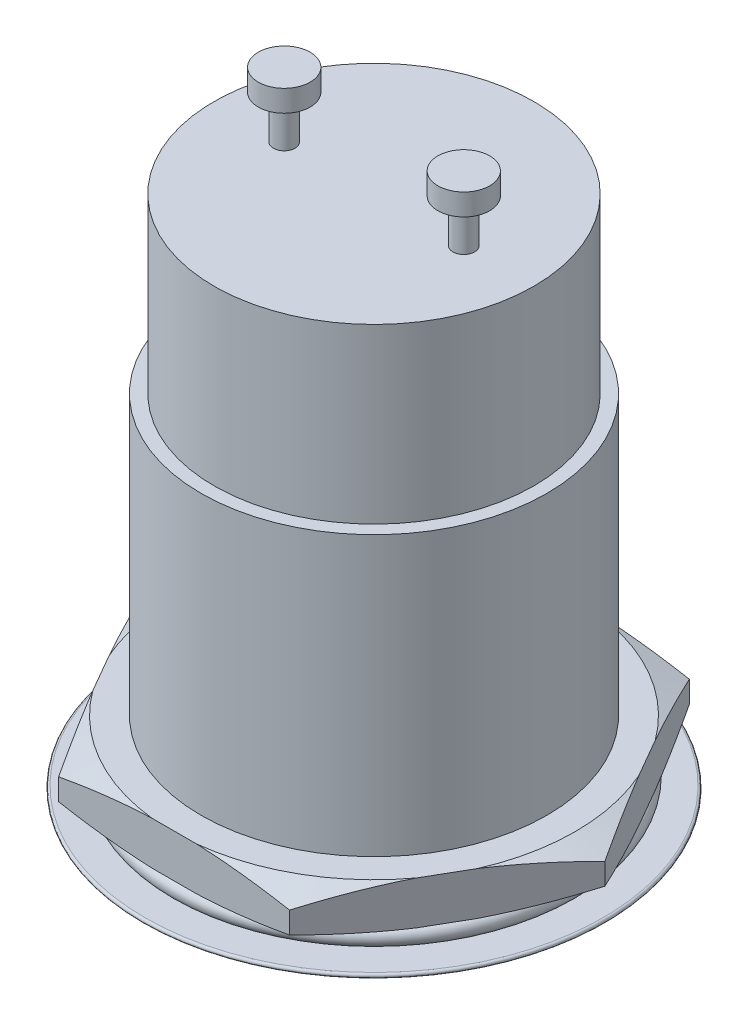
SolidWorks part; units mm, degrees
ref_plane "前视基准面" through (0, 0, 0) normal (0, 0, 1) x (1, 0, 0)
ref_plane "上视基准面" through (0, 0, 0) normal (0, 1, 0) x (1, 0, 0)
ref_plane "右视基准面" through (0, 0, 0) normal (1, 0, 0) x (0, 0, -1)
other "Configuration Table"
sketch "草图1" plane through (0, 0, 0) normal (0, 1, 0) x (1, 0, 0)
  line L1 (10.681, 0) -> (5.3405, 9.25)
  line L2 (5.3405, 9.25) -> (-5.3405, 9.25)
  line L3 (-5.3405, 9.25) -> (-10.681, 0)
  line L4 (-10.681, 0) -> (-5.3405, -9.25)
  line L5 (-5.3405, -9.25) -> (5.3405, -9.25)
  line L6 (5.3405, -9.25) -> (10.681, 0)
  circle A0 centre (0, 0) radius 9.25 construction
  circle A1 centre (0, 0) radius 10.681
  dimension "D1" = 18.5
sketch "草图2" plane through (0, 0, 0) normal (0, 1, 0) x (1, 0, 0)
  circle A0 centre (0, 0) radius 8
  dimension "D1" = 16
extrude "凸台-拉伸1" add sketch "草图2" along normal blind 22.9
sketch "草图4" plane through (0, 0, 0) normal (0, -1, 0) x (1, 0, 0)
  circle A0 centre (0, 0) radius 10.681
extrude "凸台-拉伸3" add sketch "草图4" against normal blind 2
chamfer "倒角1" distance 0.5 angle 70 1 edges at (0, 0, -10.681)
chamfer "倒角2" distance 0.5 angle 70 1 edges at (0, 2, -10.681)
extrude "切除-拉伸1" cut sketch "草图1" along normal blind 2 contours L1 A1 | L2 A1 | L6 A1 | L5 A1 | L4 A1 | L3 A1
sketch "草图6" plane through (0, 0, 0) normal (0, 0, 1) x (1, 0, 0)
  line L0 (0, 0) -> (9, 0)
  line L1 (0, 0) -> (0, -0.8)
  line L2 (0, -0.8) -> (9, -0.8)
  arc A0 (9, -0.8) -> (9, 0) centre (9, -0.4) ccw
  dimension "D1" = 0.8
  dimension "D2" = 9
  dimension "D3" = 9
revolve "旋转1" add sketch "草图6" angle 360 about L1
sketch "草图7" plane through (0, 0, 0) normal (0, 0, 1) x (1, 0, 0)
  line L0 (0, -0.8) -> (10.6, -0.8)
  line L1 (-9, -0.8) -> (9, -0.8) construction
  line L2 (10.6471, -0.9882) -> (8.4412, -2.1647)
  line L3 (7.5, -2.4) -> (0, -2.4)
  line L4 (0, -2.4) -> (0, -0.8)
  arc A0 (10.6, -0.8) -> (10.6471, -0.9882) centre (10.6, -0.9) cw
  arc A1 (8.4412, -2.1647) -> (7.5, -2.4) centre (7.5, -0.4) cw
  point P9 (11, -0.8)
  point P12 (8, -2.4)
  dimension "D4" = 0.1
  dimension "D5" = 2
  dimension "D1" = 1.6
  dimension "D2" = 8
  dimension "D3" = 11
revolve "旋转2" add sketch "草图7" angle 360 about L4
sketch "草图9" plane through (0, 0, 0) normal (0, 0, 1) x (1, 0, 0)
  line L0 (0, 0) -> (0, 22.9) construction
  line L1 (-1.0307, 0) -> (1.0307, 0) construction
  line L2 (8, 22.9) -> (-8, 22.9) construction
  line L3 (8, 22.9) -> (7.4, 22.9)
  line L4 (7.4, 22.9) -> (7.4, 14.9)
  line L5 (7.4, 14.9) -> (8, 14.9)
  line L6 (8, 2) -> (8, 22.9) construction
  line L7 (8, 14.9) -> (8, 22.9)
  dimension "D1" = 7.4
  dimension "D2" = 8
revolve "切除-旋转1" cut sketch "草图9" angle 360 about L0
sketch "草图10" plane through (0, 0, 0) normal (0, 0, 1) x (1, 0, 0)
  line L0 (4.1539, 22.9) -> (4.6539, 22.9)
  line L1 (7.4, 22.9) -> (-7.4, 22.9) construction
  line L2 (4.6539, 22.9) -> (4.6539, 24.9)
  line L3 (4.6539, 24.9) -> (5.3539, 24.9)
  line L4 (5.3539, 24.9) -> (5.3539, 25.9)
  line L5 (4.1539, 22.9) -> (4.1539, 25.9) construction
  line L6 (5.3539, 25.9) -> (4.1539, 25.9)
  line L7 (4.1539, 22.9) -> (4.1539, 25.9)
  dimension "D1" = 3
  dimension "D2" = 1
  dimension "D3" = 0.5
  dimension "D4" = 1.2
revolve "旋转4" add sketch "草图10" angle 360 about L5
mirror "镜向1" about plane through (0, 0, 0) normal (1, 0, 0) of "旋转4"
